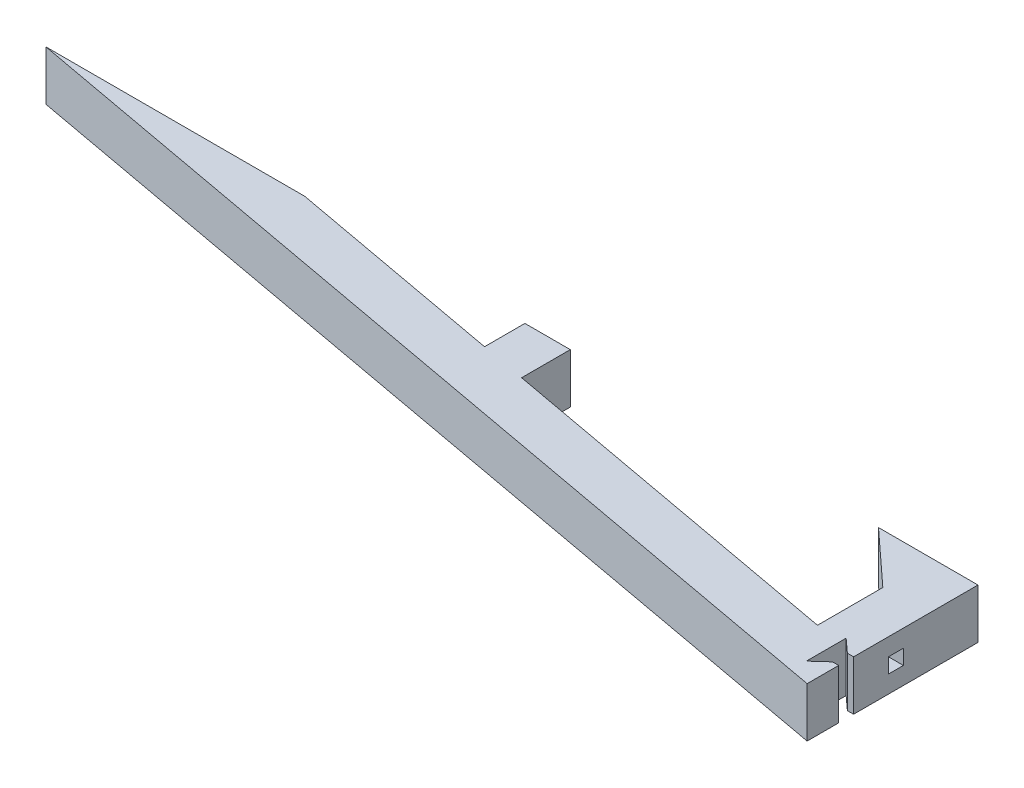
SolidWorks part; units mm, degrees
ref_plane "Přední rovina" through (0, 0, 0) normal (0, 0, 1) x (1, 0, 0)
ref_plane "Horní rovina" through (0, 0, 0) normal (0, 1, 0) x (1, 0, 0)
ref_plane "Pravá rovina" through (0, 0, 0) normal (1, 0, 0) x (0, 0, -1)
sketch "Skica2" plane through (0, 0, 0) normal (0, 1, 0) x (1, 0, 0)
  line L13 (0, 0) -> (0, -27.4721)
  line L14 (0, -27.4721) -> (-149.85, 0.0008)
  line L20 (-65.55, -7.8294) -> (-7.3, -18.5088)
  line L21 (-7.3, -18.5088) -> (-7.3, 0)
  line L22 (-7.3, 0) -> (0, 0)
  line L30 (-65.55, -7.8294) -> (-65.55, 0)
  line L31 (-65.55, 0) -> (-72.85, 0)
  line L32 (-72.85, 0) -> (-72.85, -6.4911)
  line L33 (-72.85, -6.4911) -> (-108.2597, 0.0008)
  line L34 (-108.2597, 0.0008) -> (-149.85, 0.0008)
  dimension "D1" = 27.4721
  dimension "D2" = 79.611
  dimension "D3" = 149.85
  dimension "D4" = 7.3
  dimension "D5" = 7.3
  dimension "D6" = 7.5
  dimension "D7" = 7.5
  dimension "D8" = 77
extrude "Přidat vysunutím1" add sketch "Skica2" along normal blind 8
sketch "Skica3" plane through (0, 8, 0) normal (0, 1, 0) x (1, 0, 0)
  line L6 (0, -20) -> (-1, -20)
  line L7 (0, -27.4721) -> (0, 0) construction
  line L8 (-1, -20) -> (-3.2, -18)
  line L9 (-3.2, -18) -> (-3.2, -24.4)
  line L10 (-3.2, -24.4) -> (-1, -22.4)
  line L11 (-1, -22.4) -> (0, -22.4)
  line L12 (0, -22.4) -> (0, -20)
  line L13 (0, 0) -> (-7.3, 0) construction
  dimension "D1" = 1
  dimension "D2" = 1
  dimension "D3" = 6.4
  dimension "D4" = 2.4
  dimension "D5" = 3.2
  dimension "D6" = 2
  dimension "40" = 18
extrude "Odebrat vysunutím1" cut sketch "Skica3" against normal through all
sketch "Skica5" plane through (0, 8, 0) normal (0, 1, 0) x (1, 0, 0)
  line L9 (0, 0) -> (-16, 0)
  line L16 (0, 0) -> (0, -8)
  line L17 (0, -8) -> (-16, -8)
  line L18 (-16, 0) -> (-16, -8)
  dimension "D1" = 8
  dimension "D2" = 16
extrude "Přidat vysunutím2" add sketch "Skica5" against normal blind 8
sketch "Skica7" plane through (0, 0, 0) normal (0, -1, 0) x (1, 0, 0)
  line L6 (-7.3, 8) -> (-16, 8)
  line L7 (-16, 8) -> (-16, 0)
  line L8 (-16, 0) -> (-7.3, 8)
extrude "Odebrat vysunutím4" cut sketch "Skica7" against normal through all
sketch "Skica4" plane through (0, 0, 0) normal (1, 0, 0) x (0, 0, -1)
  line L0 (-20, 8) -> (0, 8) construction
  line L5 (-14.4, 5.2) -> (-12, 5.2)
  line L6 (-14.4, 5.2) -> (-14.4, 2.8)
  line L7 (-14.4, 2.8) -> (-12, 2.8)
  line L8 (-12, 5.2) -> (-12, 2.8)
  line L13 (0, 8) -> (0, 0) construction
  dimension "D1" = 12
  dimension "D3" = 2.4
  dimension "D4" = 2.4
  dimension "D8" = 2.8
extrude "Odebrat vysunutím2" cut sketch "Skica4" against normal blind 4.4
sketch "Skica9" plane through (0, 0, 0) normal (0, 0, -1) x (-1, 0, 0)
  line L0 (65.55, 0) -> (72.85, 0) construction
  line L1 (0, 0) -> (16, 0) construction
  line L2 (0, 8) -> (0, 0) construction
  line L3 (65.55, 8) -> (65.55, 0) construction
  circle A0 centre (3.65, 4) radius 2.2
  circle A1 centre (69.2, 4) radius 2.2
  dimension "D1" = 4.4
  dimension "D2" = 4.4
  dimension "D3" = 4
  dimension "D4" = 4
  dimension "D5" = 3.65
  dimension "D6" = 3.65
extrude "Odebrat vysunutím5" cut sketch "Skica9" against normal blind 9.4
